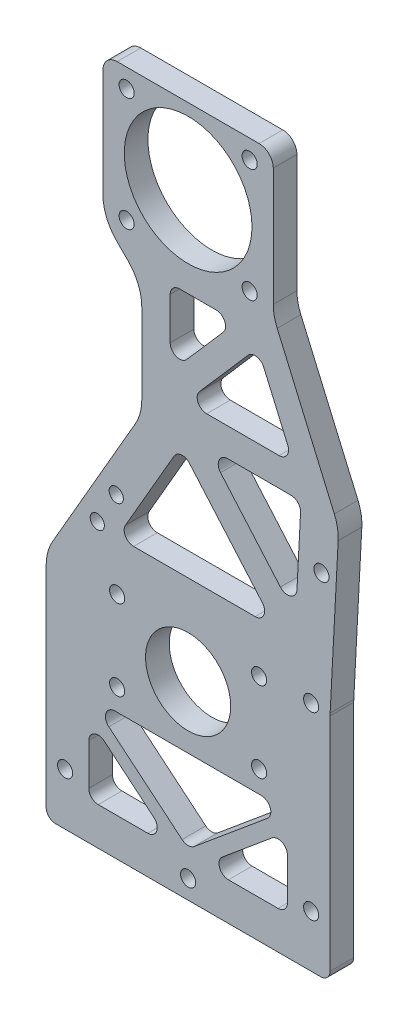
SolidWorks part; units mm, degrees
material "Thornel Mat VMA"
ref_plane "前视基准面" through (0, 0, 0) normal (0, 0, 1) x (1, 0, 0)
ref_plane "上视基准面" through (0, 0, 0) normal (0, 1, 0) x (1, 0, 0)
ref_plane "右视基准面" through (0, 0, 0) normal (1, 0, 0) x (0, 0, -1)
sketch "草图1" plane through (0, 0, 0) normal (0, 0, 1) x (1, 0, 0)
  line L0 (0, 0) -> (0, 130) construction
  line L3 (28, 0) -> (-28, 0)
  line L6 (-30, 2) -> (-30, 46.3205)
  line L7 (-28.6603, 51.3205) -> (-11.1325, 81.6795)
  line L8 (30, 2) -> (30, 48.7381)
  line L9 (30.0137, 49.2615) -> (31.7116, 81.6596)
  line L10 (-18, 143) -> (-18, 120.1421)
  line L12 (-15, 146) -> (15, 146)
  line L13 (18, 143) -> (18, 118.0691)
  line L14 (18.8211, 114.1008) -> (30.9043, 86.1512)
  line L15 (-9.7927, 86.6795) -> (-9.7927, 103.6506)
  line L18 (-15.0711, 113.0711) -> (-12.7217, 110.7217)
  circle A0 centre (0, 130) radius 13.5
  arc A6 (15, 146) -> (18, 143) centre (15, 143) cw
  arc A7 (-18, 143) -> (-15, 146) centre (-15, 143) cw
  arc A8 (30, 48.7381) -> (30.0137, 49.2615) centre (40, 48.7381) cw
  arc A9 (18, 118.0691) -> (18.8211, 114.1008) centre (28, 118.0691) ccw
  arc A10 (31.7116, 81.6596) -> (30.9043, 86.1512) centre (21.7253, 82.1829) ccw
  arc A11 (-30, 46.3205) -> (-28.6603, 51.3205) centre (-20, 46.3205) cw
  arc A12 (-11.1325, 81.6795) -> (-9.7927, 86.6795) centre (-19.7927, 86.6795) ccw
  arc A13 (-12.7217, 110.7217) -> (-9.7927, 103.6506) centre (-19.7927, 103.6506) cw
  arc A14 (-18, 120.1421) -> (-15.0711, 113.0711) centre (-8, 120.1421) ccw
  circle A15 centre (-26, 11) radius 1.6
  circle A16 centre (0, 4) radius 1.6
  circle A17 centre (26, 11) radius 1.6
  arc A18 (30, 2) -> (28, 0) centre (28, 2) cw
  arc A19 (-28, 0) -> (-30, 2) centre (-28, 2) cw
  circle A22 centre (-13, 142) radius 1.6
  circle A23 centre (13, 142) radius 1.6
  circle A24 centre (13, 118) radius 1.6
  circle A25 centre (-13, 118) radius 1.6
  point P31 (18, 146)
  point P34 (-18, 146)
  point P37 (30, 49)
  point P40 (18, 116)
  point P43 (31.8343, 84)
  point P46 (-30, 49)
  point P49 (-9.7927, 84)
  point P54 (-18, 116)
  point P64 (30, 0)
  point P67 (-30, 0)
  dimension "D2" = 27
  dimension "D3" = 30
  dimension "D16" = 3.2
  dimension "D17" = 3.2
  dimension "D18" = 3.2
  dimension "D19" = 3.2
  dimension "D20" = 3
  dimension "D21" = 10
  dimension "D22" = 3.2
  dimension "D23" = 3.2
  dimension "D24" = 3.2
  dimension "D25" = 2
  dimension "D1" = 130
  dimension "D4" = 30
  dimension "D5" = 49
  dimension "D6" = 30
  dimension "D7" = 49
  dimension "D8" = 3
  dimension "D9" = 35
  dimension "D10" = 18
  dimension "D11" = 18
  dimension "D12" = 16
  dimension "D13" = 30
  dimension "D14" = 30
  dimension "D15" = 45
extrude "凸台-拉伸1" add sketch "草图1" along normal blind 5
sketch "草图2" plane through (0, 0, 5) normal (0, 0, 1) x (1, 0, 0)
  line L0 (0, 0) -> (0, 130) construction
  line L1 (0, 40) -> (20.2429, 40) construction
  circle A0 centre (0, 40) radius 9
  circle A1 centre (-15, 48.5) radius 1.6
  circle A2 centre (15, 48.5) radius 1.6
  circle A3 centre (15, 31.5) radius 1.6
  circle A4 centre (-15, 31.5) radius 1.6
  dimension "D1" = 40
  dimension "D2" = 18
  dimension "D3" = 15
  dimension "D5" = 3.2
  dimension "D4" = 8.5
extrude "切除-拉伸1" cut sketch "草图2" against normal through all
sketch "草图3" plane through (0, 0, 5) normal (0, 0, 1) x (1, 0, 0)
  line L0 (0, 0) -> (0, 196.4366) construction
  line L1 (-28, 0) -> (28, 0) construction
  line L2 (-21, 23) -> (-21, 8)
  line L3 (-21, 8) -> (-3, 8)
  line L4 (-3, 8) -> (-21, 23)
  line L5 (-30, 46.3205) -> (-30, 2) construction
  line L6 (0, 9.4051) -> (-21, 26.9051)
  line L7 (21, 8) -> (3, 8)
  line L8 (21, 23) -> (21, 8)
  line L9 (3, 8) -> (21, 23)
  line L10 (-21, 26.9051) -> (21, 26.9051)
  line L11 (0, 9.4051) -> (21, 26.9051)
  line L12 (-14.9889, 59) -> (18.5464, 59)
  line L13 (22.7397, 63.3236) -> (23.8757, 85)
  line L14 (23.8757, 85) -> (3.9889, 85)
  line L16 (3.9889, 85) -> (0.0222, 85) construction
  line L17 (30.0137, 49.2615) -> (31.7116, 81.6596) construction
  line L18 (0.0222, 85) -> (22.5131, 59) construction
  line L19 (-1.5655, 82.2499) -> (18.5464, 59)
  line L20 (3.9889, 85) -> (22.7397, 63.3236)
  line L21 (-1.5655, 82.2499) -> (-14.9889, 59)
  line L22 (18.5464, 59) -> (22.5131, 59) construction
  line L23 (22.7397, 63.3236) -> (22.5131, 59) construction
  line L24 (-1.5655, 82.2499) -> (0.0222, 85) construction
  line L25 (-11.1325, 81.6795) -> (-28.6603, 51.3205) construction
  line L26 (-3.7927, 111) -> (-3.7927, 94.8067)
  line L27 (-0.4776, 91) -> (22.2713, 91)
  line L28 (22.2713, 91) -> (14.7247, 108.4562)
  line L29 (10.3098, 111) -> (-3.7927, 111)
  line L30 (-9.7927, 103.6506) -> (-9.7927, 86.6795) construction
  line L31 (30.9043, 86.1512) -> (18.8211, 114.1008) construction
  line L32 (-3.7927, 91) -> (13.6249, 111) construction
  line L33 (10.3098, 111) -> (-3.7927, 94.8067)
  line L34 (14.7247, 108.4562) -> (-0.4776, 91)
  line L35 (10.3098, 111) -> (13.6249, 111) construction
  line L36 (13.6249, 111) -> (14.7247, 108.4562) construction
  line L37 (-3.7927, 94.8067) -> (-3.7927, 91) construction
  line L38 (-3.7927, 91) -> (-0.4776, 91) construction
  circle A0 centre (0, 40) radius 9 construction
  point P17 (0, 26.9051)
  dimension "D1" = 8
  dimension "D2" = 9
  dimension "D3" = 3
  dimension "D4" = 15
  dimension "D5" = 3
  dimension "D6" = 19
  dimension "D7" = 8
  dimension "D8" = 8
  dimension "D9" = 26
  dimension "D10" = 3
  dimension "D11" = 3
  dimension "D12" = 6
  dimension "D13" = 6
  dimension "D14" = 6
  dimension "D15" = 20
  dimension "D16" = 2.5
  dimension "D17" = 2.5
extrude "切除-拉伸2" cut sketch "草图3" against normal through all
fillet "圆角1" radius 2 9 edges at (21, 26.9051, 2.5) (-21, 26.9051, 2.5) (-21, 23, 2.5) (-21, 8, 2.5) (-3, 8, 2.5) (0, 9.4051, 2.5) (3, 8, 2.5) (21, 23, 2.5) (21, 8, 2.5)
fillet "圆角2" radius 2 12 edges at (-3.7927, 111, 2.5) (10.3098, 111, 2.5) (-3.7927, 94.8067, 2.5) (-0.4776, 91, 2.5) (22.2713, 91, 2.5) (14.7247, 108.4562, 2.5) (23.8757, 85, 2.5) (22.7397, 63.3236, 2.5) (3.9889, 85, 2.5) (-1.5655, 82.2499, 2.5) (-14.9889, 59, 2.5) (18.5464, 59, 2.5)
sketch "草图4" plane through (0, 0, 5) normal (0, 0, 1) x (1, 0, 0)
  circle A0 centre (25.993, 49.0951) radius 1.6 construction
  circle A1 centre (28.1719, 74) radius 1.6 construction
  circle A2 centre (-19.1962, 59.7128) radius 1.5 construction
  circle A3 centre (-15.1962, 66.641) radius 1.5 construction
  circle A4 centre (25.993, 49.0951) radius 1.6
  circle A5 centre (28.1719, 74) radius 1.6
  circle A6 centre (-19.1962, 59.7128) radius 1.5
  circle A7 centre (-15.1962, 66.641) radius 1.5
extrude "切除-拉伸3" cut sketch "草图4" against normal through all
